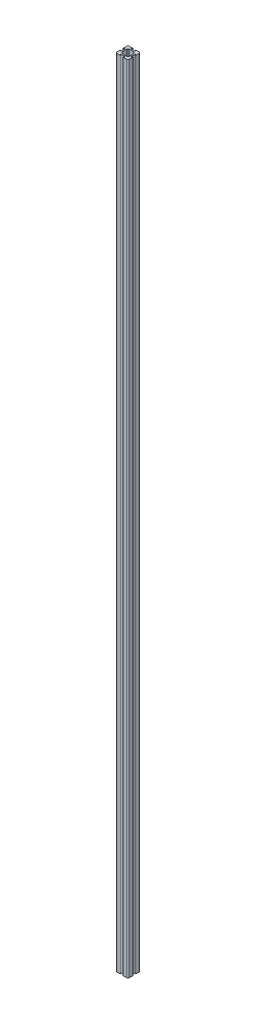
SolidWorks part; units mm, degrees
ref_plane "Front Plane" through (0, 0, 0) normal (0, 0, 1) x (1, 0, 0)
ref_plane "Top Plane" through (0, 0, 0) normal (0, 1, 0) x (1, 0, 0)
ref_plane "Right Plane" through (0, 0, 0) normal (1, 0, 0) x (0, 0, -1)
sketch "Sketch1" plane through (0, 0, 0) normal (0, 1, 0) x (1, 0, 0)
  line L0 (-12.5, 0) -> (12.5, 0) construction
  line L5 (-9.5, 12.5) -> (-2.5, 12.5)
  line L6 (0, -12.5) -> (0, 12.5) construction
  line L11 (-2.5, 12.5) -> (2.5, 12.5) construction
  line L12 (2.5, 12.5) -> (9.5, 12.5)
  line L13 (12.5, 9.5) -> (12.5, 2.5)
  line L14 (12.5, 2.5) -> (12.5, -2.5) construction
  line L15 (12.5, -2.5) -> (12.5, -9.5)
  line L16 (9.5, -12.5) -> (2.5, -12.5)
  line L17 (2.5, -12.5) -> (-2.5, -12.5) construction
  line L18 (-2.5, -12.5) -> (-9.5, -12.5)
  line L19 (-12.5, -9.5) -> (-12.5, -2.5)
  line L20 (-12.5, -2.5) -> (-12.5, 2.5) construction
  line L21 (-12.5, 2.5) -> (-12.5, 9.5)
  line L22 (-12.5, -2.5) -> (-10, -5)
  line L23 (-10, -5) -> (-10, 5)
  line L24 (-10, 5) -> (-12.5, 2.5)
  line L25 (-2.5, 12.5) -> (-5, 10)
  line L26 (-5, 10) -> (5, 10)
  line L27 (5, 10) -> (2.5, 12.5)
  line L28 (12.5, 2.5) -> (10, 5)
  line L29 (10, 5) -> (10, -5)
  line L30 (10, -5) -> (12.5, -2.5)
  line L31 (-2.5, -12.5) -> (-5, -10)
  line L32 (-5, -10) -> (5, -10)
  line L33 (5, -10) -> (2.5, -12.5)
  line L34 (-7.5, 5) -> (-5, 7.5)
  line L39 (-5, 7.5) -> (5, 7.5)
  line L40 (5, 7.5) -> (7.5, 5)
  line L41 (7.5, 5) -> (7.5, -5)
  line L42 (7.5, -5) -> (5, -7.5)
  line L43 (5, -7.5) -> (-5, -7.5)
  line L44 (-5, -7.5) -> (-7.5, -5)
  line L45 (-7.5, -5) -> (-7.5, 5)
  arc A0 (-9.5, -12.5) -> (-12.5, -9.5) centre (-9.5, -9.5) cw
  arc A1 (12.5, -9.5) -> (9.5, -12.5) centre (9.5, -9.5) cw
  arc A2 (9.5, 12.5) -> (12.5, 9.5) centre (9.5, 9.5) cw
  arc A3 (-9.5, 12.5) -> (-12.5, 9.5) centre (-9.5, 9.5) ccw
  point P2 (0, 0)
  point P6 (0, 0)
  point P44 (-7.5, 0)
  dimension "D3" = 3
  dimension "D1" = 25
  dimension "D2" = 5
  dimension "D4" = 5
  dimension "D5" = 45
  dimension "D6" = 2.5
  dimension "D7" = 2.5
extrude "Boss-Extrude1" add sketch "Sketch1" along normal blind 1600
